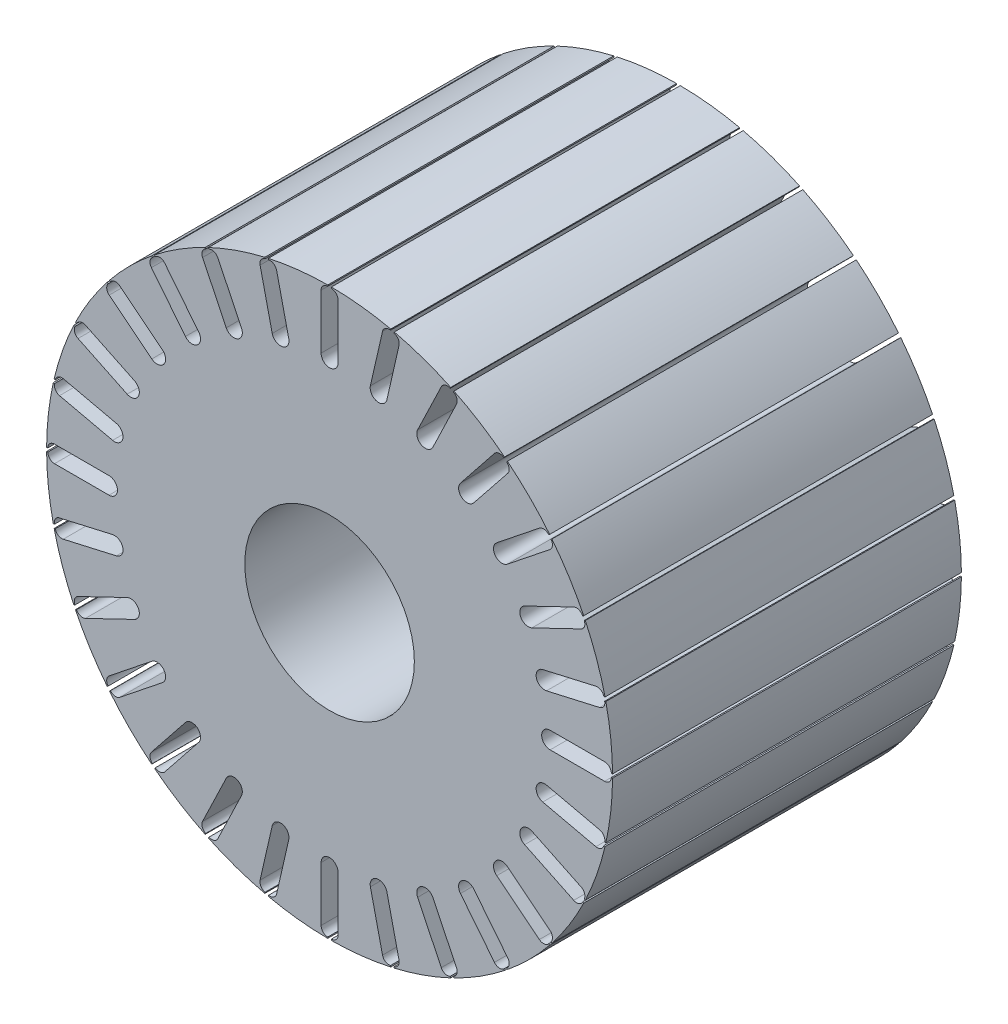
SolidWorks part; units mm, degrees
material "Ductile Iron"
ref_plane "Front Plane" through (0, 0, 0) normal (0, 0, 1) x (1, 0, 0)
ref_plane "Top Plane" through (0, 0, 0) normal (0, 1, 0) x (1, 0, 0)
ref_plane "Right Plane" through (0, 0, 0) normal (1, 0, 0) x (0, 0, -1)
sketch "Sketch1" plane through (0, 0, 0) normal (0, 0, 1) x (1, 0, 0)
  circle A0 centre (0, 0) radius 116.8
  circle A1 centre (0, 0) radius 35
  dimension "D1" = 233.6
  dimension "D2" = 70
extrude "Boss-Extrude1" add sketch "Sketch1" along normal mid plane 144
sketch "Sketch2" plane through (0, 0, 72) normal (0, 0, 1) x (1, 0, 0)
  line L0 (0, 0) -> (116.8, 0) construction
  line L1 (116.8, -0.75) -> (116.8, 0.75)
  line L2 (116.8, 0.75) -> (116.2976, 0.75)
  line L3 (113.5476, 3.5) -> (91.0476, 3.5)
  line L4 (113.5476, -3.5) -> (91.0476, -3.5)
  line L5 (116.8, -0.75) -> (116.2976, -0.75)
  circle A0 centre (0, 0) radius 116.8 construction
  arc A1 (116.2976, 0.75) -> (113.5476, 3.5) centre (113.5476, 0.75) ccw
  arc A2 (91.0476, 3.5) -> (87.5476, 0) centre (91.0476, 0) ccw
  arc A3 (91.0476, -3.5) -> (87.5476, 0) centre (91.0476, 0) cw
  arc A4 (116.2976, -0.75) -> (113.5476, -3.5) centre (113.5476, -0.75) cw
  circle A5 centre (0, 0) radius 116.8
  point P20 (116.8, 0)
  dimension "D1" = 1.5
  dimension "D2" = 7
  dimension "D3" = 7
  dimension "D4" = 22.5
  dimension "D5" = 0.5
  dimension "D6" = 0
extrude "Cut-Extrude1" cut sketch "Sketch2" against normal up to next contours A3 A2 L3 A1 L2 L1 L5 A4 L4
pattern_circular "CirPattern1" count 28 over 360 about axis through (0, 0, 0) along (0, 0, 1) of "Cut-Extrude1"
sketch "Sketch3" [suppressed] plane through (0, 0, 125) normal (0, 0, 1) x (1, 0, 0)
  line L0 (0, 38) -> (0, 0)
  line L1 (0, 0) -> (38, 0)
  arc A0 (38, 0) -> (0, 38) centre (0, 0) cw
  circle A1 centre (0, 0) radius 38 construction
equation "\"Dr\"= 233.6'outer"
equation "\"D1@Sketch1\"=\"Dr\""
equation "\"Di\"= 70'inner"
equation "\"D2@Sketch1\"=\"Di\""
equation "\"Bs0\"= 1.5"
equation "\"D1@Sketch2\"=\"Bs0\""
equation "\"Bs1\"= 7"
equation "\"D2@Sketch2\"=\"Bs1\""
equation "\"Bs2\"= 7"
equation "\"D3@Sketch2\"=\"Bs2\""
equation "\"Hs2\"= 22.5"
equation "\"D4@Sketch2\"=\"Hs2\""
equation "\"Hs0\"= 0.5"
equation "\"D5@Sketch2\"=\"Hs0\""
equation "\"Hs01\"= 0"
equation "\"D6@Sketch2\"=\"Hs01\""
